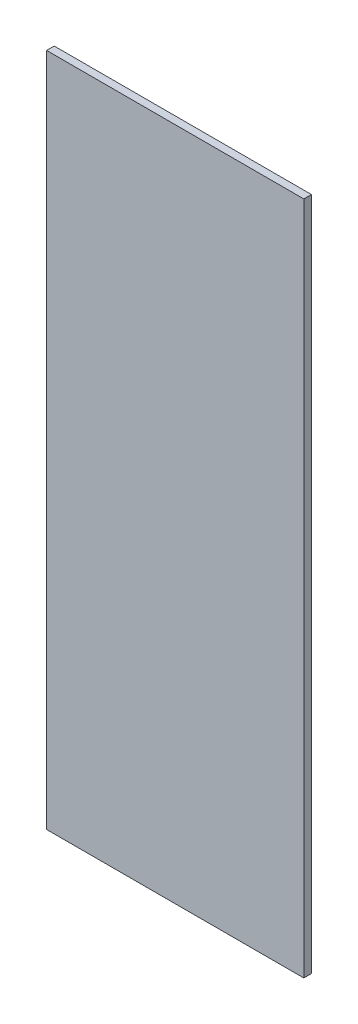
SolidWorks part; units mm, degrees
ref_plane "Plano frontal" through (0, 0, 0) normal (0, 0, 1) x (1, 0, 0)
ref_plane "Plano superior" through (0, 0, 0) normal (0, 1, 0) x (1, 0, 0)
ref_plane "Plano direito" through (0, 0, 0) normal (1, 0, 0) x (0, 0, -1)
sketch "Esboço1" plane through (0, 0, 0) normal (0, 0, 1) x (1, 0, 0)
  line L0 (168.5, 442) -> (-168.5, -442) construction
  line L1 (-168.5, 442) -> (168.5, 442)
  line L2 (-168.5, 442) -> (-168.5, -442)
  line L3 (-168.5, -442) -> (168.5, -442)
  line L4 (168.5, 442) -> (168.5, -442)
  dimension "D1" = 884
  dimension "D2" = 337
extrude "Ressalto-extrusão1" add sketch "Esboço1" along normal blind 10
